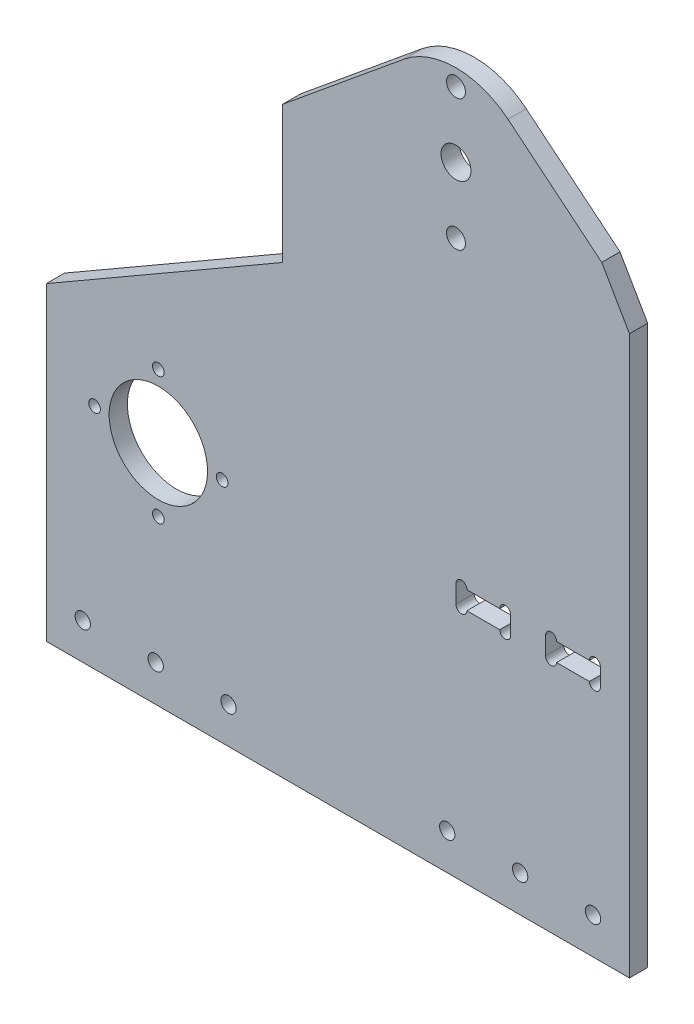
SolidWorks part; units mm, degrees
ref_plane "前视基准面" through (0, 0, 0) normal (0, 0, 1) x (1, 0, 0)
ref_plane "上视基准面" through (0, 0, 0) normal (0, 1, 0) x (1, 0, 0)
ref_plane "右视基准面" through (0, 0, 0) normal (1, 0, 0) x (0, 0, -1)
sketch "草图1" plane through (0, 0, 0) normal (0, 0, 1) x (1, 0, 0)
  line L0 (-38.379, 0) -> (39.5961, 0) construction
  line L1 (0, 25.5421) -> (0, -18.8856) construction
  line L2 (-42.831, 7.053) -> (-8.3812, 20.8807)
  line L8 (42.831, 7.053) -> (8.3812, 20.8807)
  line L10 (-47.6, 0) -> (-47.6, -170)
  line L11 (47.6, 0) -> (47.6, -170)
  line L12 (-47.6, -170) -> (47.6, -170)
  line L21 (-63.3089, -160) -> (98.3367, -160) construction
  line L22 (-47.6, -150) -> (47.6, -150) construction
  line L23 (-37.6, -150) -> (-37.6, -25) construction
  line L24 (37.6, -150) -> (37.6, -25) construction
  line L25 (-37.6, -87.5) -> (37.6, -87.5) construction
  line L26 (-37.6, -25) -> (37.6, -25) construction
  circle A0 centre (-40, 0) radius 2.6
  circle A1 centre (40, 0) radius 2.6
  arc A5 (-42.831, 7.053) -> (-47.6, 0) centre (-40, 0) ccw
  arc A6 (42.831, 7.053) -> (47.6, 0) centre (40, 0) cw
  circle A8 centre (-40, 0) radius 7.6 construction
  arc A9 (8.3812, 20.8807) -> (-8.3812, 20.8807) centre (0, 0) ccw
  circle A10 centre (40, 0) radius 7.6 construction
  circle A42 centre (0, 0) radius 4.1
  dimension "D1" = 5.2
  dimension "D2" = 40
  dimension "D4" = 22.5
  dimension "D18" = 8.2
  dimension "D3" = 5
  dimension "D10" = 170
  dimension "D11" = 10
  dimension "D14" = 10
  dimension "D15" = 10
  dimension "D17" = 25
extrude "凸台-拉伸1" add sketch "草图1" along normal blind 5
sketch "草图2" plane through (0, 0, 5) normal (0, 0, 1) x (1, 0, 0)
  line L0 (-121.9368, -107.5) -> (-62.5624, -107.5) construction
  line L1 (-81.6624, -76.7722) -> (-81.6624, -120.5738) construction
  line L2 (0, 0) -> (-81.6624, -107.5) construction
  line L3 (0, 0) -> (0, -147.3039) construction
  line L4 (47.6, -130) -> (-141.3804, -130) construction
  line L5 (-47.6, -47.5877) -> (-47.6, -150)
  line L6 (-47.6, -150) -> (-112.4, -150)
  line L7 (-112.4, -150) -> (-112.4, -85)
  line L8 (-112.4, -85) -> (-47.6, -47.5877)
  line L9 (-47.6, -170) -> (47.6, -170) construction
  line L10 (-47.6, 0) -> (-47.6, -170) construction
  circle A0 centre (-81.6624, -107.5) radius 13.5
  circle A1 centre (-81.6624, -90) radius 1.6
  circle A2 centre (-64.1624, -107.5) radius 1.6
  circle A3 centre (-81.6624, -125) radius 1.6
  circle A4 centre (-99.1624, -107.5) radius 1.6
  point P26 (0, 0)
  dimension "D1" = 27
  dimension "D3" = 3.2
  dimension "D13" = 3.2
  dimension "D14" = 3.2
  dimension "D15" = 3.2
  dimension "D2" = 17.5
  dimension "D4" = 5
  dimension "D5" = 135
  dimension "D6" = 120
  dimension "D7" = 65
  dimension "D8" = 20
  dimension "D9" = 122.4123
  dimension "D10" = 37.222
  dimension "D11" = 17.5
  dimension "D12" = 17.5
  dimension "D16" = 17.5
extrude "凸台-拉伸2" add sketch "草图2" against normal blind 5
sketch "草图3" plane through (0, 0, 5) normal (0, 0, 1) x (1, 0, 0)
  line L0 (-14.2871, 17.3818) -> (-47.6, -10)
  line L1 (14.2871, 17.3818) -> (47.6, -10)
  line L3 (-47.6, -10) -> (-95.9693, 101.0603)
  line L4 (-95.9693, 101.0603) -> (-90.3072, 103.5263)
  line L5 (-90.3072, 103.5263) -> (99.4811, 68.8424)
  line L6 (99.4811, 68.8424) -> (47.6, -10)
  line L7 (-47.6, 0) -> (-47.6, -47.5877) construction
  line L8 (47.6, -170) -> (47.6, 0) construction
  arc A0 (14.2871, 17.3818) -> (-14.2871, 17.3818) centre (0, 0) ccw
  circle A1 centre (0, 18) radius 2.6
  circle A2 centre (0, -18) radius 2.6
  arc A3 (8.3812, 20.8807) -> (-8.3812, 20.8807) centre (0, 0) ccw construction
  dimension "D1" = 10
  dimension "D2" = 5.2
  dimension "D3" = 5.2
  dimension "D4" = 36
  dimension "D5" = 18
extrude "切除-拉伸1" cut sketch "草图3" against normal blind 10
sketch "草图4" plane through (0, 0, 5) normal (0, 0, 1) x (1, 0, 0)
  line L2 (47.6, -10) -> (20.0769, 12.6229)
  line L3 (47.6, -10) -> (53.4269, -16.4917)
  line L4 (14.2871, 17.3818) -> (47.6, -10) construction
  arc A0 (20.0769, 12.6229) -> (53.4269, -16.4917) centre (17.6, -23.8724) cw
  dimension "D2" = 30
sketch "草图5" plane through (0, 0, 5) normal (0, 0, 1) x (1, 0, 0)
  line L0 (0, 53.9354) -> (0, -53.9354) construction
  line L1 (40, -3.7531) -> (47.6, -16.9167)
  line L2 (47.6, -10) -> (20.0769, 12.6229) construction
  line L3 (47.6, -170) -> (47.6, -10) construction
  line L4 (47.6, -16.9167) -> (47.6, -10)
  line L5 (47.6, -10) -> (40, -3.7531)
  point P5 (0, 0)
  dimension "D1" = 30
  dimension "D2" = 40
extrude "切除-拉伸3" cut sketch "草图5" against normal blind 5
sketch "草图6" plane through (0, 0, 5) normal (0, 0, 1) x (1, 0, 0)
  line L0 (47.6, -170) -> (47.6, -16.9167) construction
  line L1 (0, -100) -> (15, -100) construction
  line L2 (0, -100) -> (0, -105)
  line L3 (0, -105) -> (15, -105) construction
  line L4 (15, -100) -> (15, -105) construction
  line L5 (24.6, -105) -> (39.6, -105) construction
  line L6 (24.6, -105) -> (24.6, -100)
  line L7 (24.6, -100) -> (39.6, -100) construction
  line L8 (39.6, -105) -> (39.6, -100)
  line L9 (19.8, -49.4911) -> (19.8, -85.7815) construction
  circle A0 centre (38.1, -100) radius 1.5
  circle A1 centre (26.1, -100) radius 1.5
  circle A2 centre (26.1, -105) radius 1.5
  circle A3 centre (38.1, -105) radius 1.5
  circle A4 centre (1.5, -105) radius 1.5
  circle A5 centre (1.5, -100) radius 1.5
  circle A6 centre (13.5, -100) radius 1.5
  circle A7 centre (13.5, -105) radius 1.5
  dimension "D7" = 3
  dimension "D1" = 100
  dimension "D2" = 5
  dimension "D3" = 15
  dimension "D4" = 5
  dimension "D5" = 15
  dimension "D6" = 8
  dimension "D10" = 4.8
  dimension "D8" = 2
  dimension "D9" = 2
extrude "切除-拉伸5" cut sketch "草图6" against normal through all contours A4 | A5 | A7 | A6 | A3 | A2 | A1 | A0
sketch "草图7" plane through (0, 0, 5) normal (0, 0, 1) x (1, 0, 0)
  line L1 (0.0005, -100.0379) -> (14.9995, -100.0379)
  line L2 (0.0005, -100.0379) -> (0.0005, -105.0379)
  line L3 (0.0005, -105.0379) -> (14.9995, -105.0379)
  line L4 (14.9995, -100.0379) -> (14.9995, -105.0379)
  line L5 (24.6005, -100.0379) -> (39.5995, -100.0379)
  line L6 (24.6005, -100.0379) -> (24.6005, -105.0379)
  line L7 (24.6005, -105.0379) -> (39.5995, -105.0379)
  line L8 (39.5995, -100.0379) -> (39.5995, -105.0379)
  circle A0 centre (1.5, -105) radius 1.5 construction
  circle A1 centre (13.5, -105) radius 1.5 construction
  circle A2 centre (1.5, -100) radius 1.5 construction
  circle A3 centre (13.5, -100) radius 1.5 construction
  circle A4 centre (26.1, -100) radius 1.5 construction
  circle A5 centre (38.1, -105) radius 1.5 construction
  point P6 (0.0343, -60.3188)
  point P7 (0, -60)
  point P10 (14.9953, -64.8819)
  point P11 (15, -65)
  point P12 (0.0002, -85.0245)
  point P13 (0, 0)
  point P14 (24.6002, -80.0245)
  point P17 (24.8272, -85.0245)
  point P20 (0.1868, -105.7248)
  point P21 (15, -100)
  point P24 (0, -105)
  dimension "D1" = 5
  dimension "D2" = 14.999
extrude "切除-拉伸6" cut sketch "草图7" against normal through all contours L2 L1 L4 L3 | L6 L5 L8 L7
sketch "草图8" plane through (0, 0, 5) normal (0, 0, 1) x (1, 0, 0)
  line L1 (-47.6, -150) -> (-112.4, -150)
  line L2 (-47.6, -150) -> (-47.6, -170)
  line L3 (-47.6, -170) -> (-112.4, -170)
  line L4 (-112.4, -150) -> (-112.4, -170)
  point P4 (-47.6, -145)
  dimension "D1" = 64.8
  dimension "D2" = 20
extrude "凸台-拉伸3" add sketch "草图8" against normal blind 5
sketch "草图9" plane through (0, 0, 5) normal (0, 0, 1) x (1, 0, 0)
  line L0 (47.6, -170) -> (47.6, -16.9167) construction
  line L1 (-112.4, -170) -> (47.6, -170) construction
  line L2 (-32.4, -170) -> (-32.4, -87.677) construction
  line L3 (-112.4, -170) -> (47.6, -170) construction
  line L4 (-112.4, -85) -> (-112.4, -170) construction
  circle A0 centre (-102.4, -160) radius 2.1
  circle A1 centre (-82.4, -160) radius 2.1
  circle A2 centre (-62.4, -160) radius 2.1
  circle A3 centre (-2.4, -160) radius 2.1
  circle A4 centre (17.6, -160) radius 2.1
  circle A5 centre (37.6, -160) radius 2.1
  dimension "D1" = 10
  dimension "D2" = 4.2
  dimension "D3" = 10
  dimension "D5" = 20
  dimension "D6" = 10
  dimension "D4" = 3
extrude "切除-拉伸7" cut sketch "草图9" against normal blind 5
